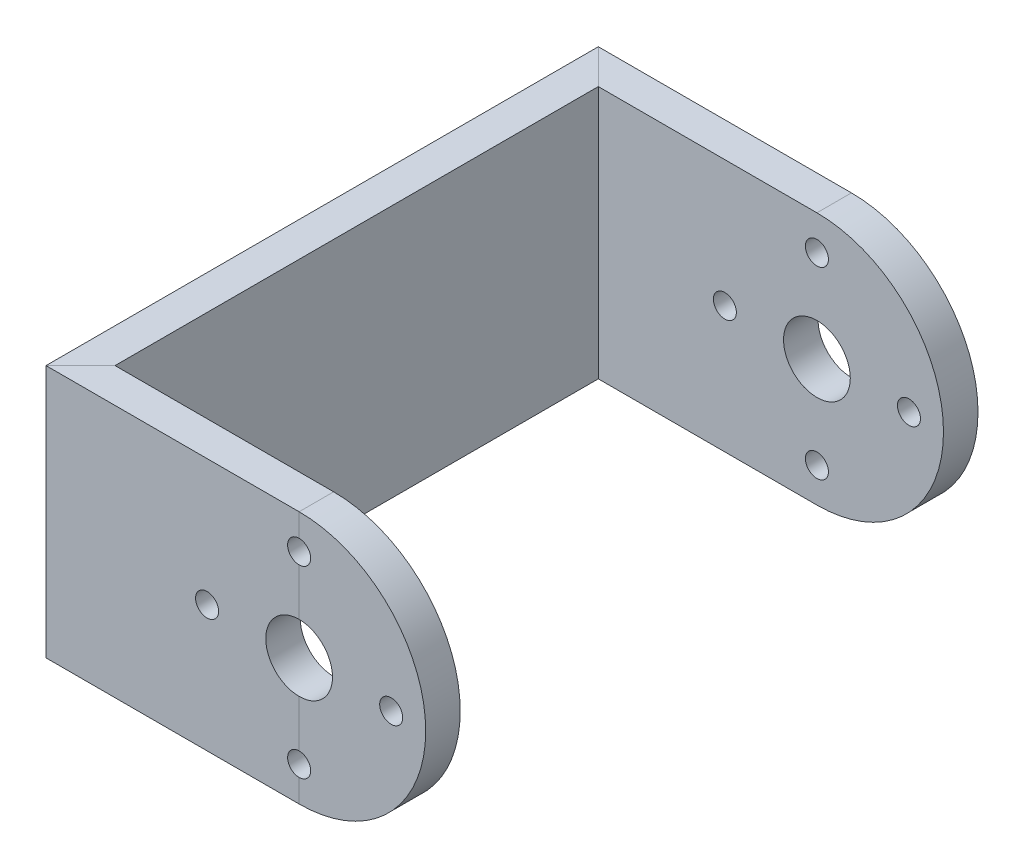
SolidWorks part; units mm, degrees
ref_plane "Front" through (0, 0, 0) normal (0, 0, 1) x (1, 0, 0)
ref_plane "Top" through (0, 0, 0) normal (0, 1, 0) x (1, 0, 0)
ref_plane "Right" through (0, 0, 0) normal (1, 0, 0) x (0, 0, -1)
sketch "Sketch2" plane through (0, 0, 0) normal (0, 1, 0) x (1, 0, 0)
  line L0 (0, 21) -> (-19, 21)
  line L1 (-19, 21) -> (-19, -21)
  line L2 (-19, -21) -> (0, -21)
  line L3 (0, -21) -> (0, 21) construction
  line L4 (0, -21) -> (11, -21)
  line L5 (0, 21) -> (11, 21)
  line L6 (11, 21) -> (11, -21) construction
  point P4 (0, 0)
  dimension "D1" = 42
  dimension "D2" = 19
  dimension "D3" = 11
sketch "Sketch3" plane through (0, 0, 0) normal (1, 0, 0) x (0, 0, -1)
  line L1 (21, 11) -> (24, 11)
  line L2 (21, 11) -> (21, -11)
  line L3 (21, -11) -> (24, -11)
  line L4 (24, 11) -> (24, -11)
  point P4 (23.1147, 5.1391)
  dimension "D1" = 3
  dimension "D2" = 22
sweep "Sweep1" add profiles "Sketch3" path "Sketch2"
sketch "Sketch1" plane through (0, 0, 0) normal (0, 0, 1) x (1, 0, 0)
  line L0 (0, 11) -> (11, 11)
  line L1 (11, 11) -> (11, 0)
  line L2 (11, -11) -> (11, 11) construction
  line L3 (11, 0) -> (11, -11)
  line L4 (11, -11) -> (0, -11)
  arc A0 (0, -11) -> (0, 11) centre (0, 0) ccw
  circle A1 centre (0, 0) radius 2.9
  circle A2 centre (8, 0) radius 1
  circle A3 centre (0, 8) radius 1
  circle A4 centre (-8, 0) radius 1
  circle A5 centre (0, -8) radius 1
  circle A6 centre (0, 0) radius 8 construction
  arc A7 (0, 11) -> (0, -11) centre (0, 0) ccw construction
  dimension "D2" = 5.8
  dimension "D3" = 16
  dimension "D4" = 2
extrude "Cut-Extrude1" cut sketch "Sketch1" against normal through all both and the other way through all contours A0 L1 L0 | A2 | A5 | A1 | A0 L4 L3 | A3 | A4
